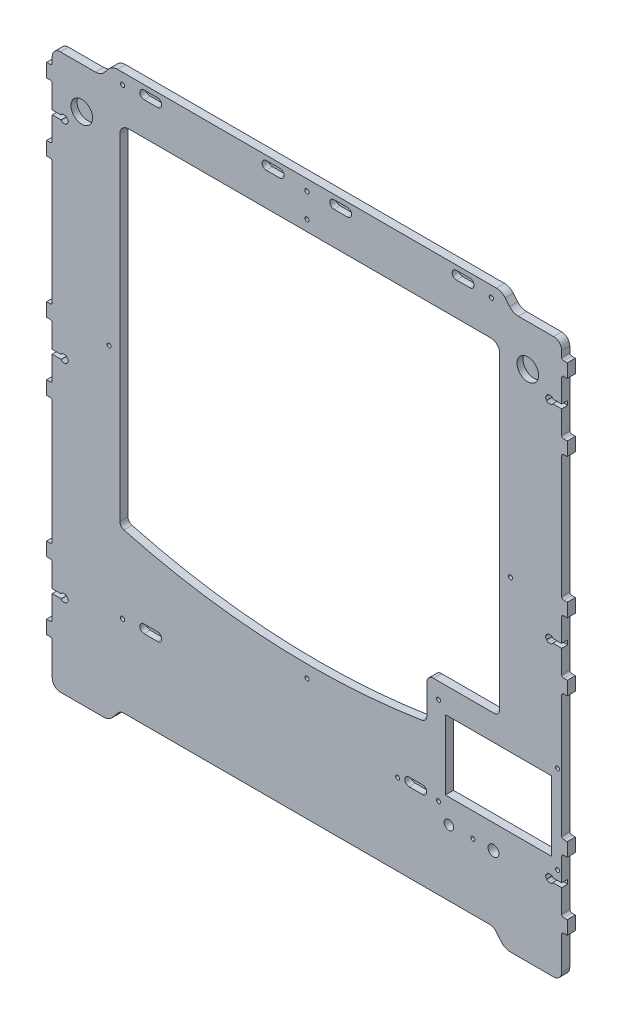
SolidWorks part; units mm, degrees
ref_plane "Alzado" through (0, 0, 0) normal (0, 0, 1) x (1, 0, 0)
ref_plane "Planta" through (0, 0, 0) normal (0, 1, 0) x (1, 0, 0)
ref_plane "Vista lateral" through (0, 0, 0) normal (1, 0, 0) x (0, 0, -1)
sketch "Croquis1" plane through (0, 0, 0) normal (0, 0, 1) x (1, 0, 0)
  line L0 (101.3953, 205.0104) -> (-166.4547, 205.0104)
  line L1 (-34.6047, 239.0104) -> (-34.6047, -170.9896) construction
  line L2 (-172.9547, 198.5104) -> (-172.9547, -49.66)
  line L3 (-222.9547, 187.3104) -> (-34.6047, 187.3104) construction
  line L4 (-128.7797, 34.0104) -> (-128.7797, 187.3104) construction
  line L5 (-222.9547, 205.7604) -> (-222.9547, 168.8604)
  line L6 (107.8953, -30.1228) -> (107.8953, 198.5104)
  line L7 (-222.9547, -87.7396) -> (-222.9547, 2.4604)
  line L8 (153.7453, -87.7396) -> (153.7453, 2.4604)
  line L9 (-227.1047, 167.3104) -> (-224.5047, 167.3104)
  line L10 (103.8762, -34.1419) -> (58.9808, -34.1419)
  line L11 (54.0552, -39.0675) -> (54.0552, -60.8574)
  line L12 (-227.1047, 157.3104) -> (-227.1047, 167.3104)
  line L13 (-224.5047, 157.3104) -> (-227.1047, 157.3104)
  line L14 (-224.5047, -89.2896) -> (-227.1047, -89.2896)
  line L15 (-227.1047, -89.2896) -> (-227.1047, -99.2896)
  line L16 (-34.6047, 34.0104) -> (-222.9547, 34.0104) construction
  line L17 (-227.1047, -99.2896) -> (-224.5047, -99.2896)
  line L21 (-227.1047, -139.2896) -> (-224.5047, -139.2896)
  line L22 (-227.1047, -149.2896) -> (-227.1047, -139.2896)
  line L23 (-224.5047, -149.2896) -> (-227.1047, -149.2896)
  line L25 (-222.9547, -137.7396) -> (-222.9547, -100.8396)
  line L32 (147.7453, -180.9896) -> (115.7453, -180.9896)
  line L36 (100.8221, -170.9896) -> (-170.0314, -170.9896)
  line L37 (-210.4105, 34.0104) -> (-223.8121, 34.0104) construction
  line L38 (-222.9547, 15.5604) -> (-222.9547, 52.4604)
  line L42 (153.7453, 37.4611) -> (153.7453, -87.7396) construction
  line L43 (-227.1047, 14.0104) -> (-224.5047, 14.0104)
  line L44 (-227.1047, 4.0104) -> (-227.1047, 14.0104)
  line L45 (-224.5047, 4.0104) -> (-227.1047, 4.0104)
  line L46 (-224.5047, 64.0104) -> (-227.1047, 64.0104)
  line L47 (-227.1047, 64.0104) -> (-227.1047, 54.0104)
  line L48 (-227.1047, 54.0104) -> (-224.5047, 54.0104)
  line L63 (-34.6047, 34.0104) -> (153.7453, 34.0104) construction
  line L69 (109.234, -177.9533) -> (105.0418, -172.9573)
  line L73 (-222.9547, 155.7604) -> (-222.9547, 65.5604)
  line L74 (-222.9547, 37.4611) -> (-222.9547, -87.7396) construction
  line L75 (-222.9547, -150.8396) -> (-222.9547, -174.9896)
  line L77 (153.7453, -150.8396) -> (153.7453, -174.9896)
  line L81 (157.8953, -99.2896) -> (155.2953, -99.2896)
  line L82 (157.8953, -89.2896) -> (157.8953, -99.2896)
  line L83 (155.2953, -89.2896) -> (157.8953, -89.2896)
  line L84 (155.2953, -149.2896) -> (157.8953, -149.2896)
  line L85 (157.8953, -149.2896) -> (157.8953, -139.2896)
  line L86 (157.8953, -139.2896) -> (155.2953, -139.2896)
  line L87 (153.7453, -137.7396) -> (153.7453, -100.8396)
  line L91 (155.2953, 4.0104) -> (157.8953, 4.0104)
  line L92 (157.8953, 4.0104) -> (157.8953, 14.0104)
  line L93 (157.8953, 14.0104) -> (155.2953, 14.0104)
  line L103 (153.7453, 15.5604) -> (153.7453, 52.4604)
  line L104 (157.8953, 54.0104) -> (155.2953, 54.0104)
  line L105 (157.8953, 64.0104) -> (157.8953, 54.0104)
  line L106 (155.2953, 64.0104) -> (157.8953, 64.0104)
  line L107 (153.7453, 155.7604) -> (153.7453, 65.5604)
  line L108 (155.2953, 157.3104) -> (157.8953, 157.3104)
  line L109 (157.8953, 157.3104) -> (157.8953, 167.3104)
  line L110 (157.8953, 167.3104) -> (155.2953, 167.3104)
  line L115 (153.7453, 205.7604) -> (153.7453, 168.8604)
  line L116 (157.8953, 207.3104) -> (155.2953, 207.3104)
  line L117 (157.8953, 217.3104) -> (157.8953, 207.3104)
  line L118 (155.2953, 217.3104) -> (157.8953, 217.3104)
  line L119 (153.7453, 223.1104) -> (153.7453, 218.8604)
  line L120 (121.7453, 229.1104) -> (147.7453, 229.1104)
  line L121 (112.0224, 235.9741) -> (115.234, 232.1467)
  line L131 (105.511, 239.0104) -> (-174.7203, 239.0104)
  line L132 (-181.2317, 235.9741) -> (-184.4433, 232.1467)
  line L133 (-190.9547, 229.1104) -> (-216.9547, 229.1104)
  line L134 (-222.9547, 223.1104) -> (-222.9547, 218.8604)
  line L135 (-224.5047, 217.3104) -> (-227.1047, 217.3104)
  line L136 (-227.1047, 217.3104) -> (-227.1047, 207.3104)
  line L137 (-227.1047, 207.3104) -> (-224.5047, 207.3104)
  line L142 (-216.9547, -180.9896) -> (-184.9547, -180.9896)
  line L143 (-178.4433, -177.9533) -> (-174.2511, -172.9573)
  line L145 (-222.9547, 110.6604) -> (-34.6047, 110.6604) construction
  arc A0 (-172.9547, -49.66) -> (-169.9851, -53.6034) centre (-168.8516, -49.66) ccw
  arc A1 (107.8953, 198.5104) -> (101.3953, 205.0104) centre (101.3953, 198.5104) ccw
  arc A2 (-222.9547, 168.8604) -> (-224.5047, 167.3104) centre (-224.5047, 168.8604) cw
  arc A3 (-224.5047, 157.3104) -> (-222.9547, 155.7604) centre (-224.5047, 155.7604) cw
  arc A4 (-166.4547, 205.0104) -> (-172.9547, 198.5104) centre (-166.4547, 198.5104) ccw
  arc A5 (103.8762, -34.1419) -> (107.8953, -30.1228) centre (103.8762, -30.1228) ccw
  arc A7 (-224.5047, -89.2896) -> (-222.9547, -87.7396) centre (-224.5047, -87.7396) ccw
  arc A8 (-222.9547, -100.8396) -> (-224.5047, -99.2896) centre (-224.5047, -100.8396) ccw
  arc A9 (-222.9547, -137.7396) -> (-224.5047, -139.2896) centre (-224.5047, -137.7396) cw
  arc A10 (50.2783, -65.2775) -> (-169.9851, -53.6034) centre (-32.4058, 458.4336) cw
  arc A11 (50.2783, -65.2775) -> (54.0552, -60.8574) centre (49.5804, -60.8574) ccw
  arc A12 (58.9808, -34.1419) -> (54.0552, -39.0675) centre (58.9808, -39.0675) ccw
  arc A15 (-224.5047, -149.2896) -> (-222.9547, -150.8396) centre (-224.5047, -150.8396) cw
  arc A18 (-222.9547, -174.9896) -> (-216.9547, -180.9896) centre (-216.9547, -174.9896) ccw
  arc A28 (-222.9547, 15.5604) -> (-224.5047, 14.0104) centre (-224.5047, 15.5604) cw
  arc A29 (-224.5047, 4.0104) -> (-222.9547, 2.4604) centre (-224.5047, 2.4604) cw
  arc A30 (-224.5047, 64.0104) -> (-222.9547, 65.5604) centre (-224.5047, 65.5604) ccw
  arc A31 (-222.9547, 52.4604) -> (-224.5047, 54.0104) centre (-224.5047, 52.4604) ccw
  arc A40 (100.8221, -170.9896) -> (105.0418, -172.9573) centre (100.8221, -176.498) cw
  arc A41 (115.7453, -180.9896) -> (109.234, -177.9533) centre (115.7453, -172.4896) cw
  arc A42 (153.7453, -174.9896) -> (147.7453, -180.9896) centre (147.7453, -174.9896) cw
  arc A45 (153.7453, -100.8396) -> (155.2953, -99.2896) centre (155.2953, -100.8396) cw
  arc A62 (155.2953, -89.2896) -> (153.7453, -87.7396) centre (155.2953, -87.7396) cw
  arc A63 (155.2953, -149.2896) -> (153.7453, -150.8396) centre (155.2953, -150.8396) ccw
  arc A64 (153.7453, -137.7396) -> (155.2953, -139.2896) centre (155.2953, -137.7396) ccw
  arc A68 (155.2953, 4.0104) -> (153.7453, 2.4604) centre (155.2953, 2.4604) ccw
  arc A69 (153.7453, 15.5604) -> (155.2953, 14.0104) centre (155.2953, 15.5604) ccw
  circle A70 centre (101.7453, 231.0104) radius 1.6
  circle A71 centre (-34.6047, 231.0104) radius 1.6
  arc A75 (153.7453, 52.4604) -> (155.2953, 54.0104) centre (155.2953, 52.4604) cw
  arc A76 (155.2953, 64.0104) -> (153.7453, 65.5604) centre (155.2953, 65.5604) cw
  arc A77 (155.2953, 157.3104) -> (153.7453, 155.7604) centre (155.2953, 155.7604) ccw
  arc A78 (153.7453, 168.8604) -> (155.2953, 167.3104) centre (155.2953, 168.8604) ccw
  arc A83 (153.7453, 205.7604) -> (155.2953, 207.3104) centre (155.2953, 205.7604) cw
  arc A84 (155.2953, 217.3104) -> (153.7453, 218.8604) centre (155.2953, 218.8604) cw
  arc A85 (147.7453, 229.1104) -> (153.7453, 223.1104) centre (147.7453, 223.1104) cw
  arc A86 (121.7453, 229.1104) -> (115.234, 232.1467) centre (121.7453, 237.6104) cw
  arc A87 (105.511, 239.0104) -> (112.0224, 235.9741) centre (105.511, 230.5104) cw
  arc A89 (-174.7203, 239.0104) -> (-181.2317, 235.9741) centre (-174.7203, 230.5104) ccw
  arc A90 (-190.9547, 229.1104) -> (-184.4433, 232.1467) centre (-190.9547, 237.6104) ccw
  arc A91 (-216.9547, 229.1104) -> (-222.9547, 223.1104) centre (-216.9547, 223.1104) ccw
  arc A92 (-224.5047, 217.3104) -> (-222.9547, 218.8604) centre (-224.5047, 218.8604) ccw
  arc A93 (-222.9547, 205.7604) -> (-224.5047, 207.3104) centre (-224.5047, 205.7604) ccw
  arc A97 (-184.9547, -180.9896) -> (-178.4433, -177.9533) centre (-184.9547, -172.4896) ccw
  arc A98 (-170.0314, -170.9896) -> (-174.2511, -172.9573) centre (-170.0314, -176.498) ccw
  circle A108 centre (-170.9547, 231.0104) radius 1.6
  circle A133 centre (-170.9547, -110.9896) radius 1.6
  dimension "D1" = 8.5
  dimension "D3" = 8.5
  dimension "D4" = 6
  dimension "D8" = 1.55
  dimension "D11" = 1.55
  dimension "D14" = 50
  dimension "D21" = 6
  dimension "D23" = 40
  dimension "D26" = 8
  dimension "D27" = 32
  dimension "D29" = 3.2
  dimension "D30" = 8.5
  dimension "D7" = 3.2
  dimension "D20" = 13
  dimension "D87" = 1.55
  dimension "D88" = 1.55
  dimension "D22" = 13
  dimension "D2" = 50
  dimension "D5" = 8
  dimension "D6" = 52
  dimension "D9" = 10
  dimension "D10" = 2.6
  dimension "D13" = 50
  dimension "D16" = 34
  dimension "D17" = 11.8
  dimension "D18" = 32
  dimension "D19" = 15.9
  dimension "D28" = 52
  dimension "D32" = 10
  dimension "D33" = 6.5218
  dimension "D34" = 50
  dimension "D85" = 10
  dimension "D86" = 2.6
extrude "Saliente-Extruir1" add sketch "Croquis1" along normal blind 6
sketch "Croquis10" plane through (0, 0, 6) normal (0, 0, 1) x (1, 0, 0)
  line L0 (153.7453, 205.7604) -> (153.7453, 168.8604) construction
  line L2 (101.7453, -110.9896) -> (183.8923, -110.9896) construction
  line L3 (-216.4544, 188.8604) -> (-222.9547, 188.8604)
  line L4 (-209.8753, 187.3104) -> (-223.8121, 187.3104) construction
  line L5 (-214.9445, 190.0604) -> (-213.3945, 190.0604)
  line L6 (-211.8813, 188.8465) -> (-211.8813, 188.6773)
  line L7 (-222.9547, 34.0104) -> (153.7453, 34.0104) construction
  line L8 (-211.8813, 185.9436) -> (-211.8813, 185.7743)
  line L9 (-214.9445, 184.5604) -> (-213.3945, 184.5604)
  line L10 (-222.9547, 188.8604) -> (-222.9547, 185.7604)
  line L11 (-34.6047, 239.0104) -> (-34.6047, -170.9896) construction
  line L12 (105.511, 239.0104) -> (-174.7203, 239.0104) construction
  line L13 (100.8221, -170.9896) -> (-170.0314, -170.9896) construction
  line L14 (-222.9547, 15.5604) -> (-222.9547, 52.4604) construction
  line L15 (-216.4544, 185.7604) -> (-222.9547, 185.7604)
  line L16 (-222.9547, 110.6604) -> (-34.6047, 110.6604) construction
  line L17 (-222.9547, 155.7604) -> (-222.9547, 65.5604) construction
  line L18 (-209.8753, 34.0104) -> (-223.8121, 34.0104) construction
  line L19 (-216.4544, 35.5604) -> (-222.9547, 35.5604)
  line L20 (-222.9547, 32.4604) -> (-222.9547, 35.5604)
  line L21 (-214.9445, 36.7604) -> (-213.3945, 36.7604)
  line L22 (-211.8813, 35.3773) -> (-211.8813, 35.5465)
  line L23 (-211.8813, 32.4743) -> (-211.8813, 32.6436)
  line L24 (-214.9445, 31.2604) -> (-213.3945, 31.2604)
  line L25 (-216.4544, 32.4604) -> (-222.9547, 32.4604)
  line L26 (-209.8753, -119.2896) -> (-223.8121, -119.2896) construction
  line L27 (-216.4544, -117.7396) -> (-222.9547, -117.7396)
  line L28 (-222.9547, -120.8396) -> (-222.9547, -117.7396)
  line L29 (-214.9445, -116.5396) -> (-213.3945, -116.5396)
  line L30 (-211.8813, -117.9227) -> (-211.8813, -117.7535)
  line L31 (-211.8813, -120.8257) -> (-211.8813, -120.6564)
  line L32 (-214.9445, -122.0396) -> (-213.3945, -122.0396)
  line L33 (-216.4544, -120.8396) -> (-222.9547, -120.8396)
  line L34 (140.666, -119.2896) -> (154.6028, -119.2896) construction
  line L35 (147.2451, -120.8396) -> (153.7453, -120.8396)
  line L36 (145.7352, -122.0396) -> (144.1852, -122.0396)
  line L37 (142.672, -120.8257) -> (142.672, -120.6564)
  line L38 (142.672, -117.9227) -> (142.672, -117.7535)
  line L39 (145.7352, -116.5396) -> (144.1852, -116.5396)
  line L40 (153.7453, -120.8396) -> (153.7453, -117.7396)
  line L41 (147.2451, -117.7396) -> (153.7453, -117.7396)
  line L42 (140.666, 34.0104) -> (154.6028, 34.0104) construction
  line L43 (147.2451, 32.4604) -> (153.7453, 32.4604)
  line L44 (145.7352, 31.2604) -> (144.1852, 31.2604)
  line L45 (142.672, 32.4743) -> (142.672, 32.6436)
  line L46 (142.672, 35.3773) -> (142.672, 35.5465)
  line L47 (145.7352, 36.7604) -> (144.1852, 36.7604)
  line L48 (153.7453, 32.4604) -> (153.7453, 35.5604)
  line L49 (147.2451, 35.5604) -> (153.7453, 35.5604)
  line L50 (140.666, 187.3104) -> (154.6028, 187.3104) construction
  line L51 (147.2451, 185.7604) -> (153.7453, 185.7604)
  line L52 (153.7453, 188.8604) -> (153.7453, 185.7604)
  line L53 (145.7352, 184.5604) -> (144.1852, 184.5604)
  line L54 (142.672, 185.9436) -> (142.672, 185.7743)
  line L55 (142.672, 188.8465) -> (142.672, 188.6773)
  line L56 (145.7352, 190.0604) -> (144.1852, 190.0604)
  line L57 (147.2451, 188.8604) -> (153.7453, 188.8604)
  line L58 (-64.6047, 235.6104) -> (-54.6047, 235.6104)
  line L59 (-64.6047, 229.4104) -> (-54.6047, 229.4104)
  line L60 (153.7453, 15.5604) -> (153.7453, 52.4604) construction
  line L61 (-155.1047, 235.6104) -> (-145.1047, 235.6104)
  line L62 (-155.1047, 229.4104) -> (-145.1047, 229.4104)
  line L63 (-54.6047, 229.4104) -> (-145.1047, 229.4104) construction
  line L64 (-4.6047, 229.4104) -> (-14.6047, 229.4104)
  line L65 (-4.6047, 235.6104) -> (-14.6047, 235.6104)
  line L66 (85.8953, 235.6104) -> (75.8953, 235.6104)
  line L67 (85.8953, 229.4104) -> (75.8953, 229.4104)
  line L68 (153.7453, -137.7396) -> (153.7453, -100.8396) construction
  line L69 (150.7453, -110.9896) -> (150.7453, -109.4896) construction
  line L70 (-155.1047, -106.3896) -> (-145.1047, -106.3896)
  line L71 (-155.1047, -112.5896) -> (-145.1047, -112.5896)
  line L72 (150.7453, -45.9896) -> (150.4025, -45.9896) construction
  line L73 (62.7453, -45.9896) -> (62.7453, -110.9896) construction
  line L76 (-54.6047, 229.4104) -> (-59.2707, -112.5578) construction
  line L77 (71.4025, -45.9896) -> (33.4932, -45.9896) construction
  line L78 (-190.9547, 229.1104) -> (-216.9547, 229.1104) construction
  line L79 (-227.1047, 64.0104) -> (-227.1047, 54.0104) construction
  line L80 (-227.1047, 59.0104) -> (157.8953, 59.0104) construction
  line L81 (157.8953, 64.0104) -> (157.8953, 54.0104) construction
  line L82 (-222.9547, 205.7604) -> (-222.9547, 168.8604) construction
  line L83 (-4.6047, -112.5896) -> (-14.6047, -112.5896) [skipped]
  line L84 (-4.6047, -106.3896) -> (-14.6047, -106.3896) [skipped]
  line L85 (-64.6047, -112.5896) -> (-54.6047, -112.5896) [skipped]
  line L86 (-64.6047, -106.3896) -> (-54.6047, -106.3896) [skipped]
  line L87 (75.8953, -106.3896) -> (28.0463, -106.3896) construction
  line L88 (150.7453, -46.4164) -> (150.7453, -27.838) construction
  line L89 (150.7374, -109.4896) -> (150.7453, -110.9896) construction
  line L90 (150.4025, -45.9896) -> (164.7294, -45.9896) construction
  line L91 (67.7453, -52.9896) -> (146.2453, -52.9896)
  line L92 (67.7453, -52.9896) -> (67.7453, -104.4896)
  line L93 (67.7453, -104.4896) -> (146.2453, -104.4896)
  line L94 (146.2453, -52.9896) -> (146.2453, -104.4896)
  line L95 (62.7453, -45.9896) -> (149.2453, -45.9896) construction
  line L96 (75.8953, -112.5896) -> (26.3993, -112.5896) construction
  line L97 (50.8953, -104.4896) -> (50.8953, -114.379) construction
  line L99 (50.8953, -106.3896) -> (40.8953, -106.3896)
  line L100 (50.8953, -112.5896) -> (40.8953, -112.5896)
  line L101 (85.8953, -106.3896) -> (75.8953, -106.3896) [skipped]
  line L102 (85.8953, -112.5896) -> (75.8953, -112.5896) [skipped]
  circle A0 centre (128.7453, 198.6104) radius 8
  circle A1 centre (-201.1047, 198.6104) radius 8
  arc A2 (-214.9445, 36.7604) -> (-216.4544, 35.5604) centre (-214.9445, 35.2104) ccw
  circle A3 centre (-170.9547, -110.9896) radius 1.6 construction
  arc A4 (-211.8813, 32.4743) -> (-213.3945, 31.2604) centre (-213.3945, 32.8104) cw
  arc A5 (-214.9445, 31.2604) -> (-216.4544, 32.4604) centre (-214.9445, 32.8104) cw
  arc A6 (-211.8813, 35.5465) -> (-213.3945, 36.7604) centre (-213.3945, 35.2104) ccw
  arc A7 (-211.8813, 35.3773) -> (-211.8813, 32.6436) centre (-212.6118, 34.0104) cw
  arc A8 (-211.8813, 185.9436) -> (-211.8813, 188.6773) centre (-212.6118, 187.3104) ccw
  arc A9 (-214.9445, -116.5396) -> (-216.4544, -117.7396) centre (-214.9445, -118.0896) ccw
  arc A10 (-211.8813, -120.8257) -> (-213.3945, -122.0396) centre (-213.3945, -120.4896) cw
  arc A11 (-214.9445, -122.0396) -> (-216.4544, -120.8396) centre (-214.9445, -120.4896) cw
  arc A12 (-211.8813, -117.7535) -> (-213.3945, -116.5396) centre (-213.3945, -118.0896) ccw
  arc A13 (-211.8813, -117.9227) -> (-211.8813, -120.6564) centre (-212.6118, -119.2896) cw
  arc A14 (142.672, -117.9227) -> (142.672, -120.6564) centre (143.4025, -119.2896) ccw
  arc A15 (142.672, -117.7535) -> (144.1852, -116.5396) centre (144.1852, -118.0896) cw
  arc A16 (145.7352, -122.0396) -> (147.2451, -120.8396) centre (145.7352, -120.4896) ccw
  arc A17 (142.672, -120.8257) -> (144.1852, -122.0396) centre (144.1852, -120.4896) ccw
  arc A18 (145.7352, -116.5396) -> (147.2451, -117.7396) centre (145.7352, -118.0896) cw
  arc A19 (142.672, 35.3773) -> (142.672, 32.6436) centre (143.4025, 34.0104) ccw
  arc A20 (142.672, 35.5465) -> (144.1852, 36.7604) centre (144.1852, 35.2104) cw
  arc A21 (145.7352, 31.2604) -> (147.2451, 32.4604) centre (145.7352, 32.8104) ccw
  arc A22 (142.672, 32.4743) -> (144.1852, 31.2604) centre (144.1852, 32.8104) ccw
  arc A23 (145.7352, 36.7604) -> (147.2451, 35.5604) centre (145.7352, 35.2104) cw
  arc A24 (145.7352, 184.5604) -> (147.2451, 185.7604) centre (145.7352, 186.1104) ccw
  arc A25 (142.672, 188.8465) -> (144.1852, 190.0604) centre (144.1852, 188.5104) cw
  arc A26 (145.7352, 190.0604) -> (147.2451, 188.8604) centre (145.7352, 188.5104) cw
  arc A27 (142.672, 185.7743) -> (144.1852, 184.5604) centre (144.1852, 186.1104) ccw
  arc A28 (142.672, 185.9436) -> (142.672, 188.6773) centre (143.4025, 187.3104) cw
  arc A29 (-54.6047, 229.4104) -> (-54.6047, 235.6104) centre (-54.6047, 232.5104) ccw
  arc A30 (-64.6047, 235.6104) -> (-64.6047, 229.4104) centre (-64.6047, 232.5104) ccw
  arc A31 (-145.1047, 229.4104) -> (-145.1047, 235.6104) centre (-145.1047, 232.5104) ccw
  arc A32 (-155.1047, 235.6104) -> (-155.1047, 229.4104) centre (-155.1047, 232.5104) ccw
  arc A33 (-14.6047, 229.4104) -> (-14.6047, 235.6104) centre (-14.6047, 232.5104) cw
  arc A34 (-4.6047, 235.6104) -> (-4.6047, 229.4104) centre (-4.6047, 232.5104) cw
  arc A35 (75.8953, 229.4104) -> (75.8953, 235.6104) centre (75.8953, 232.5104) cw
  arc A36 (85.8953, 235.6104) -> (85.8953, 229.4104) centre (85.8953, 232.5104) cw
  circle A37 centre (150.7453, -110.9896) radius 1.5
  circle A38 centre (150.7453, -45.9896) radius 1.5
  arc A39 (-145.1047, -112.5896) -> (-145.1047, -106.3896) centre (-145.1047, -109.4896) ccw
  arc A40 (-155.1047, -106.3896) -> (-155.1047, -112.5896) centre (-155.1047, -109.4896) ccw
  circle A41 centre (62.7453, -45.9896) radius 1.5
  circle A42 centre (62.7453, -110.9896) radius 1.5
  arc A45 (40.8953, -112.5896) -> (40.8953, -106.3896) centre (40.8953, -109.4896) cw
  arc A46 (50.8953, -106.3896) -> (50.8953, -112.5896) centre (50.8953, -109.4896) cw
  arc A63 (-211.8813, 185.7743) -> (-213.3945, 184.5604) centre (-213.3945, 186.1104) cw
  arc A65 (-214.9445, 190.0604) -> (-216.4544, 188.8604) centre (-214.9445, 188.5104) ccw
  arc A66 (-211.8813, 188.8465) -> (-213.3945, 190.0604) centre (-213.3945, 188.5104) ccw
  arc A67 (-214.9445, 184.5604) -> (-216.4544, 185.7604) centre (-214.9445, 186.1104) cw
  arc A68 (-14.6047, -112.5896) -> (-14.6047, -106.3896) centre (-14.6047, -109.4896) cw [skipped]
  arc A69 (-4.6047, -106.3896) -> (-4.6047, -112.5896) centre (-4.6047, -109.4896) cw [skipped]
  arc A70 (-54.6047, -112.5896) -> (-54.6047, -106.3896) centre (-54.6047, -109.4896) ccw [skipped]
  arc A71 (-64.6047, -106.3896) -> (-64.6047, -112.5896) centre (-64.6047, -109.4896) ccw [skipped]
  arc A72 (85.8953, -106.3896) -> (85.8953, -112.5896) centre (85.8953, -109.4896) cw [skipped]
  arc A73 (75.8953, -112.5896) -> (75.8953, -106.3896) centre (75.8953, -109.4896) cw [skipped]
  dimension "D4" = 6.2
  dimension "D5" = 10
  dimension "D12" = 6.5002
  dimension "D3" = 16
  dimension "D13" = 1.55
  dimension "D15" = 1.55
  dimension "D17" = 1.5498
  dimension "D9" = 40.4
  dimension "D21" = 21.85
  dimension "D26" = 3
  dimension "D27" = 65
  dimension "D28" = 88
  dimension "D29" = 65
  dimension "D6" = 20
  dimension "D7" = 6.5
  dimension "D10" = 15.85
  dimension "D14" = 1.55
  dimension "D16" = 0.1692
  dimension "D18" = 41.8
  dimension "D19" = 1.55
  dimension "D20" = 1.2
  dimension "D22" = 25
  dimension "D23" = 2.7365
  dimension "D24" = 1.3669
  dimension "D30" = 78.5
  dimension "D31" = 51.5
  dimension "D32" = 40.4
  dimension "D33" = 5
  dimension "D34" = 7
  dimension "D8" = 2
  dimension "D11" = 2
extrude "Cortar-Extruir4" cut sketch "Croquis10" against normal blind 4.5
sketch "Croquis12" plane through (0, 0, 6) normal (0, 0, 1) x (1, 0, 0)
  line L0 (146.2453, -52.9896) -> (67.7453, -52.9896) construction
  line L1 (67.7453, -52.9896) -> (67.7453, -104.4896) construction
  line L2 (146.2453, -104.4896) -> (146.2453, -52.9896) construction
  line L3 (67.7453, -104.4896) -> (146.2453, -104.4896) construction
  line L4 (146.2453, -52.9896) -> (67.7453, -52.9896)
  line L5 (67.7453, -52.9896) -> (67.7453, -104.4896)
  line L6 (146.2453, -104.4896) -> (146.2453, -52.9896)
  line L7 (67.7453, -104.4896) -> (146.2453, -104.4896)
  line L8 (62.7453, -110.9896) -> (62.7453, -146.2874) construction
  line L9 (62.7453, -122.3396) -> (113.5642, -122.3396) construction
  line L10 (62.7453, -110.9896) -> (118.9149, -110.9896) construction
  circle A0 centre (150.7453, -110.9896) radius 1.5 construction
  circle A1 centre (150.7453, -45.9896) radius 1.5 construction
  circle A2 centre (62.7453, -45.9896) radius 1.5 construction
  circle A3 centre (62.7453, -110.9896) radius 1.5 construction
  circle A4 centre (150.7453, -110.9896) radius 1.5
  circle A5 centre (150.7453, -45.9896) radius 1.5
  circle A6 centre (62.7453, -45.9896) radius 1.5
  circle A7 centre (62.7453, -110.9896) radius 1.5
  circle A8 centre (70.3453, -122.3396) radius 3.5
  circle A9 centre (88.0953, -122.3396) radius 1.5
  circle A10 centre (103.3453, -122.3396) radius 4
  dimension "D2" = 7.6
  dimension "D3" = 17.75
  dimension "D4" = 33
  dimension "D1" = 11.35
extrude "Cortar-Extruir5" cut sketch "Croquis12" against normal blind 6
sketch "Croquis13" plane through (0, 0, 6) normal (0, 0, 1) x (1, 0, 0)
  line L1 (96.4703, -107.5672) -> (108.9592, -107.5672)
  line L2 (96.4703, -107.5672) -> (96.4703, -114.7394)
  line L3 (96.4703, -114.7394) -> (108.9592, -114.7394)
  line L4 (108.9592, -107.5672) -> (108.9592, -114.7394)
extrude "Saliente-Extruir2" add sketch "Croquis13" against normal blind 6
sketch "Croquis14" plane through (0, 0, 6) normal (0, 0, 1) x (1, 0, 0)
  line L0 (62.7453, -110.9896) -> (2.0273, -110.9896) construction
  line L1 (40.8953, -106.3896) -> (40.8953, -124.7124) construction
  line L2 (32.7453, -105.4686) -> (32.7453, -121.3905) construction
  circle A0 centre (62.7453, -110.9896) radius 1.5 construction
  circle A1 centre (62.7453, -110.9896) radius 1.5
  circle A2 centre (32.3863, -110.9896) radius 1.5
  dimension "D1" = 8.15
extrude "Cortar-Extruir6" cut sketch "Croquis14" against normal blind 6
sketch "Croquis15" plane through (0, 0, 0) normal (0, 0, -1) x (-1, 0, 0)
  line L0 (34.6047, 231.0104) -> (34.6047, -170.9896) construction
  line L1 (-100.8221, -170.9896) -> (170.0314, -170.9896) construction
  line L2 (-157.8953, 59.0104) -> (237.5674, 59.0104) construction
  line L3 (-157.8953, 64.0104) -> (-157.8953, 54.0104) construction
  line L4 (-101.3953, 205.0104) -> (166.4547, 205.0104) construction
  line L5 (-107.8953, -30.1228) -> (-107.8953, 198.5104) construction
  line L6 (172.9547, 198.5104) -> (172.9547, -49.66) construction
  circle A0 centre (34.6047, 213.0104) radius 1.5
  circle A1 centre (-115.8953, 59.0104) radius 1.5
  circle A2 centre (180.9547, 59.0104) radius 1.5
  circle A3 centre (34.6047, -80.9896) radius 1.5
  dimension "D1" = 8
  dimension "D2" = 8
  dimension "D3" = 8
  dimension "D4" = 140
extrude "Cortar-Extruir7" cut sketch "Croquis15" against normal blind 6
equation "\"Ancho_panel\"= 385'Ancho del panel"
equation "\"Alto_panel\"= 420'Alto del panel izquierdo"
equation "\"Altura_base_taladros\"= 70'Alto taladros de la base eje Z"
equation "\"Altura_superior_taladros\"= 8mm'Distancia taladros a top"
equation "\"Distancia_vert_entre_horizontales_ensambles\"= \"Alto_panel\" - \"Altura_base_taladros\" - \"Altura_superior_taladros\"'Distancia vertical entre horizontales de ensambles"
equation "\"Latrales_separacion_barras_a_escalon_bajo\"= 12.5'Separación entre las barras y el escalón inferior de la parte superior"
equation "\"Espacio_tensor_correa_motor\"= 8.5mm'Espacio para mover el motor en vertical y tensar la correa"
